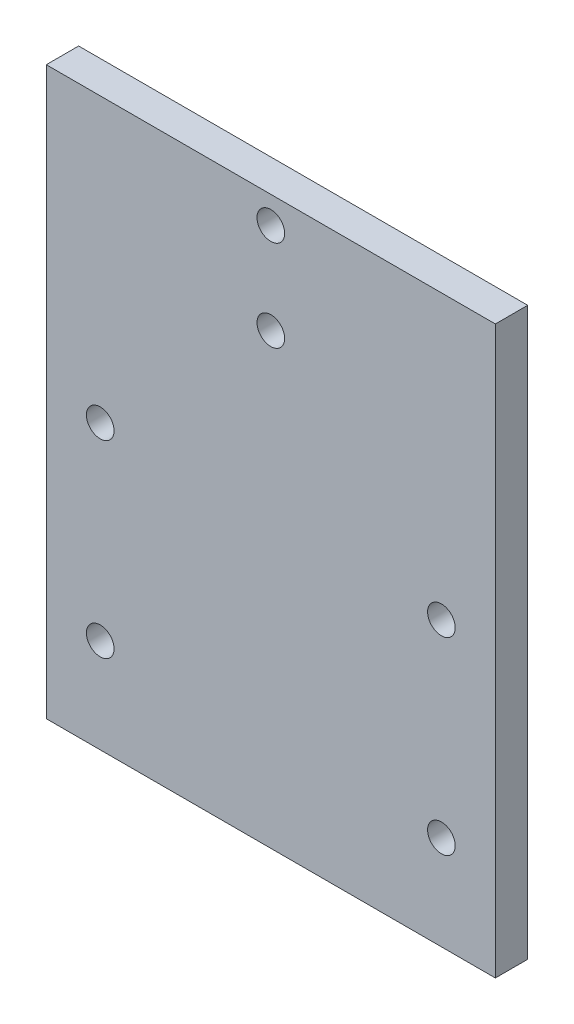
SolidWorks part; units mm, degrees
ref_plane "Front Plane" through (0, 0, 0) normal (0, 0, 1) x (1, 0, 0)
ref_plane "Top Plane" through (0, 0, 0) normal (0, 1, 0) x (1, 0, 0)
ref_plane "Right Plane" through (0, 0, 0) normal (1, 0, 0) x (0, 0, -1)
sketch "Sketch1" plane through (0, 0, 0) normal (0, 0, 1) x (1, 0, 0)
  line L1 (-16.65, -28) -> (16.65, -28)
  line L2 (-16.65, -28) -> (-16.65, 14)
  line L3 (-16.65, 14) -> (16.65, 14)
  line L4 (16.65, -28) -> (16.65, 14)
  circle A0 centre (0, 4) radius 1.3
  circle A1 centre (0, 12) radius 1.3
  point P0 (0, 0)
  dimension "D3" = 2.6
  dimension "D4" = 2.6
  dimension "D1" = 33.3
  dimension "D2" = 42
  dimension "D6" = 2
  dimension "D7" = 8
extrude "Boss-Extrude1" add sketch "Sketch1" along normal blind 2.4 contours L1 L4 L3 L2 A1 A0
sketch "Sketch2" plane through (0, 0, 0) normal (0, 0, 1) x (1, 0, 0)
  line L0 (-16.65, -28) -> (-16.65, 14) construction
  line L1 (16.65, -28) -> (16.65, 14) construction
  line L3 (-16.65, -28) -> (16.65, -28) construction
  point P0 (-12.65, -7)
  point P1 (12.65, -7)
  point P2 (12.65, -21)
  point P3 (-12.65, -21)
  point P6 (0, 4)
  point P7 (0, 12)
  point P14 (0, 0)
  dimension "D1" = 4
  dimension "D2" = 4
  dimension "D3" = 4
  dimension "D4" = 7
  dimension "D5" = 7
hole_wizard "M2.5 Tapped Hole1" positions "3DSketch1" profile "Sketch3" tap size "M2.5" standard "ISO"
sketch3d "3DSketch1"
  point P0 (0, 5.25, 0)
  point P3 (0, 12, 0)
  point P6 (-12.65, -7, 0)
  point P9 (-12.65, -21, 0)
  point P12 (12.65, -21, 0)
  point P15 (12.65, -7, 0)
  point P18 (0, 4, 0)
  point P20 (0, 12, 0)
  point P21 (0, 12, 0)
  point P23 (0, 12, 0)
  point P25 (0, 5.25, 0)
  point P31 (0, 12, 0)
  dimension "D1" = 0
  dimension "D2" = 0
  dimension "D3" = 6.75
sketch "Sketch3" plane through (0, 12, 0) normal (1, 0, 0) x (0, 1, 0)
  line L0 (0, 0) -> (0, 2.401)
  line L1 (0, 2.401) -> (1.025, 2.401)
  line L2 (1.025, 2.401) -> (1.025, 0.25)
  line L3 (1.025, 0.25) -> (1.275, 0)
  line L5 (1.275, 0) -> (0, 0)
  line L6 (-1.025, 0.25) -> (-1.275, 0) construction
  line L11 (0, -6.35) -> (0, 107.95) construction
  dimension "Thru Tap Drill Dia." = 2.05
  dimension "Thru Tap Drill Depth" = 2.401
  dimension "Near C'Sink Dia." = 2.55
  dimension "Near C'Sink Angle" = 90
cosmetic thread "Hole Thread1" parameters "D2"=2.5
cosmetic thread "Hole Thread3" parameters "D2"=2.5
cosmetic thread "Hole Thread4" parameters "D2"=2.5
cosmetic thread "Hole Thread5" parameters "D2"=2.5
cosmetic thread "Hole Thread9" parameters "D2"=2.5
cosmetic thread "Hole Thread10" parameters "D2"=2.5
cosmetic thread "Hole Thread11" parameters "D2"=2.5
cosmetic thread "Hole Thread16" parameters "D2"=2.5
cosmetic thread "Hole Thread17" parameters "D2"=2.5
cosmetic thread "Hole Thread18" parameters "D2"=2.5
cosmetic thread "Hole Thread19" parameters "D2"=2.5
cosmetic thread "Hole Thread20" parameters "D2"=2.5
